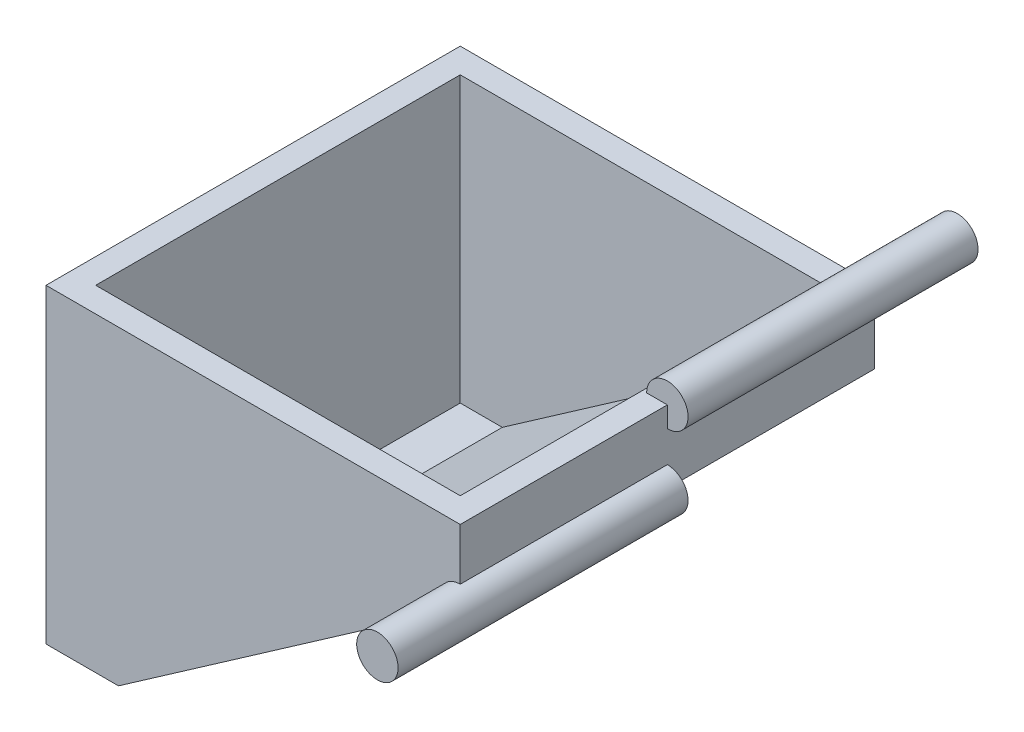
SolidWorks part; units mm, degrees
ref_plane "Front Plane" through (0, 0, 0) normal (0, 0, 1) x (1, 0, 0)
ref_plane "Top Plane" through (0, 0, 0) normal (0, 1, 0) x (1, 0, 0)
ref_plane "Right Plane" through (0, 0, 0) normal (1, 0, 0) x (0, 0, -1)
sketch "Sketch2" plane through (0, 0, 0) normal (0, 0, 1) x (1, 0, 0)
  line B0 (0, 0) -> (2000, 0)
  line B1 (2000, 0) -> (2000, -350)
  line B2 (2000, -350) -> (350, -1500)
  line B3 (350, -1500) -> (0, -1500)
  line B4 (0, -1500) -> (0, 0)
sketch_block_instance "Block22-1"
sketch_block "Block22" parameters "D1"=1500, "D2"=2000, "D3"=350, "D4"=350
sketch "Sketch3" plane through (0, 0, 0) normal (0, 0, 1) x (1, 0, 0)
  line B0 (0, 0) -> (2000, 0)
  line B1 (350, -1500) -> (0, -1500)
  line B2 (2000, 0) -> (2000, -350)
  line B3 (0, -1500) -> (0, 0)
  line B4 (2000, -350) -> (350, -1500)
sketch_block_instance "Block21-2"
sketch_block "Block21" parameters "D1"=1500, "D2"=350, "D3"=350
extrude "Boss-Extrude1" add sketch "Sketch3" along normal blind 2000
sketch "Sketch4" plane through (0, 0, 2000) normal (0, 0, 1) x (1, 0, 0)
  line L0 (120, 0) -> (120, -1372.483)
  line L1 (0, 0) -> (2000, 0) construction
  line L2 (120, -1372.483) -> (323.0929, -1372.483)
  line L3 (323.0929, -1372.483) -> (1880, -287.3659)
  line L4 (1880, -287.3659) -> (1880, -109.214)
  line L5 (1880, -109.214) -> (1880, 0)
  line L6 (1880, 0) -> (120, 0)
  line L7 (0, -1500) -> (0, 0) construction
  line L8 (2000, 0) -> (2000, -350) construction
  line L9 (2000, -350) -> (350, -1500) construction
  line L10 (350, -1500) -> (0, -1500) construction
  point P12 (2000, -175)
  dimension "D1" = 120
  dimension "D2" = 120
  dimension "D3" = 127.517
  dimension "D4" = 120
extrude "Cut-Extrude1" cut sketch "Sketch4" against normal blind 1880
sketch "Sketch5" plane through (0, 0, 2000) normal (0, 0, 1) x (1, 0, 0)
  line L0 (120, 0) -> (120, -1372.483)
  line L1 (120, -1372.483) -> (323.0929, -1372.483)
  line L2 (323.0929, -1372.483) -> (1880, -287.3659)
  line L3 (1880, -287.3659) -> (1880, 0)
  line L4 (1880, 0) -> (120, 0)
extrude "Boss-Extrude2" add sketch "Sketch5" against normal blind 120
sketch "Sketch6" plane through (0, 0, 0) normal (0, 0, -1) x (-1, 0, 0)
  circle A0 centre (-2000, 0) radius 100
  dimension "D1" = 200
extrude "Boss-Extrude3" add sketch "Sketch6" along normal blind 400 and the other way blind 1000
sketch "Sketch7" plane through (0, 0, 2000) normal (0, 0, 1) x (1, 0, 0)
  circle A0 centre (2000, -350) radius 100
  dimension "D1" = 200
extrude "Boss-Extrude4" add sketch "Sketch7" along normal blind 400 and the other way blind 1000
